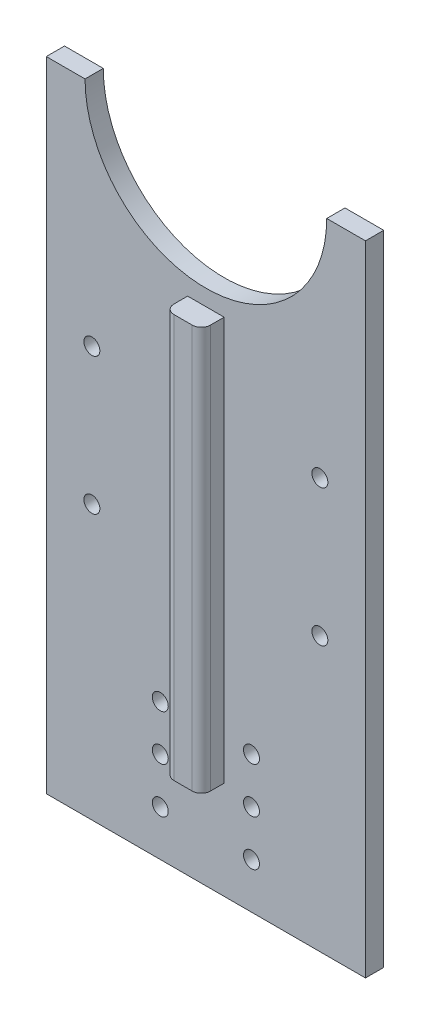
SolidWorks part; units mm, degrees
ref_plane "Front Plane" through (0, 0, 0) normal (0, 0, 1) x (1, 0, 0)
ref_plane "Top Plane" through (0, 0, 0) normal (0, 1, 0) x (1, 0, 0)
ref_plane "Right Plane" through (0, 0, 0) normal (1, 0, 0) x (0, 0, -1)
sketch "Sketch1" plane through (0, 0, 0) normal (0, 0, 1) x (1, 0, 0)
  line L0 (-26.5, 140) -> (-35, 140)
  line L1 (-35, 0) -> (35, 0)
  line L2 (-35, 0) -> (-35, 140)
  line L4 (35, 0) -> (35, 140)
  line L5 (26.5, 140) -> (35, 140)
  arc A0 (-26.5, 140) -> (26.5, 140) centre (0, 140) ccw
  circle A1 centre (-25, 60) radius 1.75
  circle A2 centre (25, 60) radius 1.75
  circle A3 centre (-10, 10) radius 1.75
  circle A4 centre (10, 10) radius 1.75
  circle A5 centre (10, 20) radius 1.75
  circle A6 centre (-10, 20) radius 1.75
  circle A7 centre (10, 30) radius 1.75
  circle A8 centre (-10, 30) radius 1.75
  dimension "D2" = 26.5
  dimension "D4" = 3.5
  dimension "D12" = 3.5
  dimension "D1" = 70
  dimension "D3" = 35
  dimension "D5" = 10
  dimension "D6" = 10
  dimension "D7" = 140
  dimension "D8" = 60
  dimension "D9" = 10
  dimension "D10" = 25
  dimension "D11" = 25
  dimension "D13" = 10
  dimension "D14" = 10
extrude "Boss-Extrude1" add sketch "Sketch1" along normal blind 4
sketch "Sketch2" plane through (0, 0, 4) normal (0, 0, 1) x (1, 0, 0)
  line L1 (-4, 21.5) -> (4, 21.5)
  line L2 (-4, 21.5) -> (-4, 110)
  line L3 (-4, 110) -> (4, 110)
  line L4 (4, 21.5) -> (4, 110)
  line L5 (-26.5, 140) -> (-35, 140) construction
  dimension "D1" = 4
  dimension "D2" = 8
  dimension "D3" = 30
  dimension "D4" = 21.5
extrude "Boss-Extrude2" add sketch "Sketch2" along normal blind 5
fillet "Fillet1" radius 2 2 edges at (-4, 65.75, 9) (4, 65.75, 9)
sketch "Sketch3" plane through (0, 0, 4) normal (0, 0, 1) x (1, 0, 0)
  circle A0 centre (-25, 90) radius 1.75
  circle A1 centre (25, 90) radius 1.75
  point P4 (0, 0)
  point P5 (0, 0)
  point P7 (0, 0)
  dimension "D2" = 3.5
  dimension "D1" = 30
extrude "Cut-Extrude1" cut sketch "Sketch3" against normal through all
